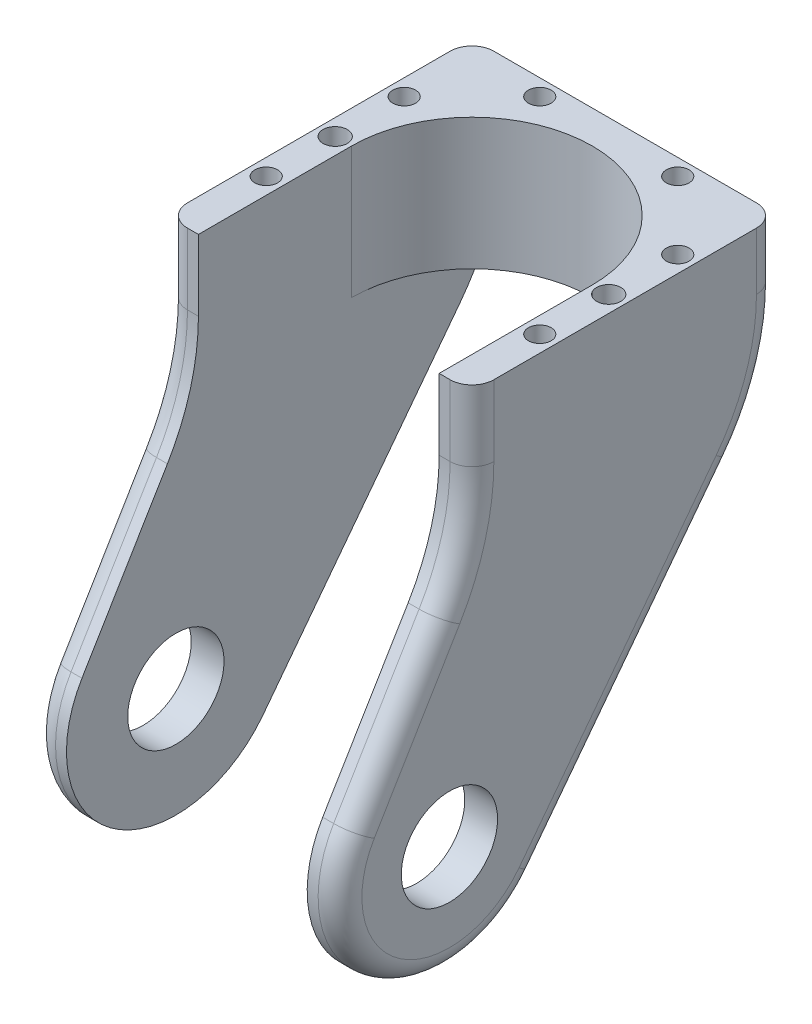
SolidWorks part; units mm, degrees
ref_plane "Front Plane" through (0, 0, 0) normal (0, 0, 1) x (1, 0, 0)
ref_plane "Top Plane" through (0, 0, 0) normal (0, 1, 0) x (1, 0, 0)
ref_plane "Right Plane" through (0, 0, 0) normal (1, 0, 0) x (0, 0, -1)
sketch "Sketch1" plane through (0, 0, 0) normal (0, 1, 0) x (1, 0, 0)
  line L1 (0, 0) -> (11.2442, 0) construction
  line L2 (-35, 0) -> (-35, -35)
  line L3 (-35, -35) -> (35, -35)
  line L4 (35, -35) -> (35, 0)
  line L5 (-35, 0) -> (-35, 35)
  line L6 (-35, 35) -> (35, 35)
  line L7 (35, 35) -> (35, 0)
  line L10 (31.25, -31.25) -> (31.25, 31.25) construction
  line L11 (31.25, 31.25) -> (-31.25, 31.25) construction
  line L12 (-31.25, 31.25) -> (-31.25, -31.25) construction
  line L13 (-31.25, -31.25) -> (31.25, -31.25) construction
  circle A0 centre (0, 0) radius 35 construction
  circle A1 centre (0, 0) radius 27.5
  circle A32 centre (0, 0) radius 31.25 construction
  circle A33 centre (-15.7913, 31.25) radius 2.6 construction
  circle A34 centre (15.7619, 31.25) radius 2.6 construction
  circle A35 centre (-31.25, 31.25) radius 2.6 construction
  circle A36 centre (31.25, 31.25) radius 2.6 construction
  circle A37 centre (31.25, -31.25) radius 2.6 construction
  circle A38 centre (-31.25, -31.25) radius 2.6 construction
  circle A39 centre (-31.25, -15.7619) radius 2.6 construction
  circle A40 centre (-31.25, 15.7619) radius 2.6 construction
  circle A41 centre (31.25, 15.7619) radius 2.6 construction
  circle A42 centre (31.25, -15.7619) radius 2.6 construction
  point P41 (0, 0)
  dimension "D1" = 70
  dimension "D2" = 55
  dimension "D3" = 62.5
  dimension "D4" = 5.2
extrude "Boss-Extrude1" add sketch "Sketch1" along normal blind 30
sketch "Sketch7" plane through (35, 0, 0) normal (1, 0, 0) x (0, 0, -1)
  line L0 (0, 10) -> (0, -49.6631) construction
  line L1 (0, 0) -> (-40.1504, -57.3406) construction
  line L2 (0, 0) -> (-35, 0) construction
  line L3 (-20.2689, -72.4974) -> (-61.6088, -44.5135) construction
  line L4 (-61.6088, -44.5135) -> (-35, 0)
  line L5 (-35, 0) -> (35, 0)
  line L6 (35, 0) -> (-20.2689, -72.4974)
  circle A0 centre (-40.1504, -57.3406) radius 11
  circle A1 centre (-40.1504, -57.3406) radius 25
  line M5 (-35, 0) -> (35, 0)
  dimension "D2" = 22
  dimension "D3" = 50
  dimension "D1" = 55
  dimension "D4" = 70
extrude "Boss-Extrude3" add sketch "Sketch7" against normal blind 70 contours A1 L6 L5 L4 M5 | A1 A0
fillet "Fillet2" radius 50 2 edges at (0, 0, -35) (0, 0, 35)
fillet "Fillet1" radius 5 14 edges at (-35, 21.9025, 35) (35, 21.9025, 35) (-35, 23.4427, -35) (35, 23.4427, -35) (35, -28.1814, 51.846) (-35, -28.1814, 51.846) (35, -78.0434, 54.1645) (-35, -78.0434, 54.1645) (-35, -42.9628, -2.247) (35, -42.9628, -2.247) (-35, 0.8876, -32.3716) (35, 0.8876, -32.3716) (-35, 0.4979, 36.8033) (35, 0.4979, 36.8033)
sketch "Sketch11" plane through (0, 30, 0) normal (0, 1, 0) x (1, 0, 0)
  line L0 (-27.5, 0) -> (-27.5, -75.9327)
  line L2 (-27.5, -75.9327) -> (27.5, -75.9327)
  line L4 (27.5, -75.9327) -> (27.5, 0)
  circle A0 centre (0, 0) radius 27.5
  circle M3 centre (0, 0) radius 27.5
  line M6 (-30, -35) -> (30, -35)
  dimension "D1" = 55
extrude "Cut-Extrude10" cut sketch "Sketch11" against normal blind 30 contours L4 L0 M6 M3 | L2 L4 L0 M6
sketch "Sketch9" plane through (0, 0, 0) normal (0, 0, 1) x (1, 0, 0)
  line L0 (-27.5, 0) -> (27.5, 0)
  line L1 (-27.5, 0) -> (-27.5, -83.6258)
  line L2 (27.5, 0) -> (27.5, -83.6258)
  line L3 (-27.5, -83.6258) -> (27.5, -83.6258)
  line L4 (-35, 0) -> (35, 0) construction
  line L6 (-37.5, 0) -> (-27.5, 0) construction
  line L7 (27.5, 0) -> (37.5, 0) construction
  line L9 (27.5, 30) -> (27.5, 13.805) construction
  line L10 (-27.5, 13.805) -> (-27.5, 30) construction
  dimension "D1" = 10
extrude "Cut-Extrude8" cut sketch "Sketch9" along normal blind 102 and the other way blind 102 contours L0 L1 L3 L2
sketch "Sketch10" plane through (0, 0, 0) normal (0, -1, 0) x (-1, 0, 0)
  line L0 (0, 0) -> (6.9504, 0) construction
  line L7 (31.25, -31.25) -> (31.25, 31.25) construction
  line L8 (31.25, 31.25) -> (-31.25, 31.25) construction
  line L13 (-31.25, 31.25) -> (-31.25, -31.25) construction
  line L14 (-31.25, -31.25) -> (31.25, -31.25) construction
  circle A15 centre (0, 0) radius 35 construction
  circle A16 centre (0, 0) radius 31.25 construction
  circle A17 centre (-15.7619, 31.25) radius 2.6
  circle A18 centre (15.7619, 31.25) radius 2.6
  circle A19 centre (-31.25, -15.7619) radius 2.6
  circle A20 centre (-31.25, 15.7619) radius 2.6
  circle A21 centre (31.25, 15.7619) radius 2.6
  circle A22 centre (31.25, -15.7619) radius 2.6
  circle A23 centre (-31.25, 0) radius 2.7692
  circle A24 centre (31.25, 0) radius 2.7692
  circle A25 centre (-20.7289, -31.25) radius 2.7692
  circle A26 centre (15.7619, -31.25) radius 2.7692
  point P30 (0, 0)
  dimension "D1" = 70
  dimension "D2" = 62.5
  dimension "D3" = 5.2
extrude "Cut-Extrude9" cut sketch "Sketch10" against normal through all both and the other way through all
